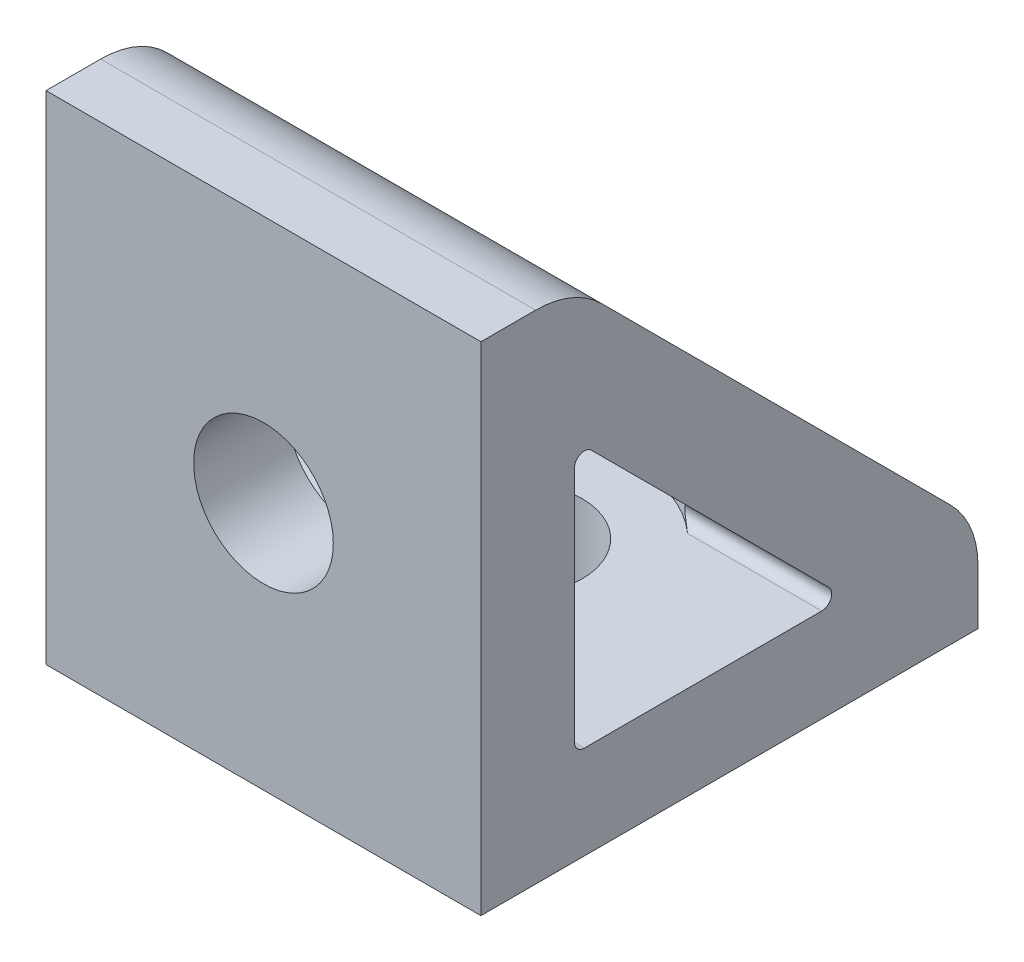
SolidWorks part; units mm, degrees
ref_plane "Front"
ref_plane "Top" through (0, 0, 0) normal (0, 1, 0) x (1, 0, 0)
ref_plane "Right" through (0, 0, 0) normal (1, 0, 0) x (0, 0, -1)
sketch "Sketch1" plane through (0, 0, 0) normal (1, 0, 0) x (0, 0, -1)
  line L0 (11.7094, 11.7094) -> (15.086, 15.086) construction
  line L1 (4.7752, 12.7) -> (0, 12.7) construction
  line L2 (11.3502, 4.7752) -> (11.3502, 0) construction
  line L8 (0, 25.4) -> (0, 0)
  line L9 (0, 0) -> (25.4, 0)
  line L10 (25.4, 0) -> (25.4, 2.794)
  line L11 (4.7752, 17.4172) -> (4.7752, 5.2832)
  line L12 (5.2832, 4.7752) -> (17.4172, 4.7752)
  line L13 (2.794, 25.4) -> (0, 25.4)
  line L14 (6.1706, 24.0014) -> (24.0014, 6.1706)
  line L15 (5.6424, 17.7764) -> (17.7764, 5.6424)
  arc A0 (4.7752, 5.2832) -> (5.2832, 4.7752) centre (5.2832, 5.2832) ccw
  arc A1 (17.4172, 4.7752) -> (17.7764, 5.6424) centre (17.4172, 5.2832) ccw
  arc A2 (5.6424, 17.7764) -> (4.7752, 17.4172) centre (5.2832, 17.4172) ccw
  arc A3 (6.1706, 24.0014) -> (2.794, 25.4) centre (2.794, 20.6248) ccw
  arc A4 (25.4, 2.794) -> (24.0014, 6.1706) centre (20.6248, 2.794) ccw
  dimension "OuterRadius" = 4.7752
  dimension "InnerRadius" = 0.508
  dimension "LengthZ" = 25.4
  dimension "HeightY" = 25.4
  dimension "Thickness" = 4.7752
  dimension "Angle" = 45
  dimension "CornerZ" = 2.794
extrude "Base Extrude" add sketch "Sketch1" against normal blind 22.225
sketch "Sketch2" plane through (0, 0, 0) normal (0, -1, 0) x (1, 0, 0)
  line L1 (-22.225, 0) -> (0, 0) construction
  line L2 (0, 0) -> (0, -25.4) construction
  circle A0 centre (-11.1125, -12.7) radius 3.5687
  dimension "D1" = 7.1374
  dimension "Hole1Z" = 12.7
  dimension "Hole1X" = 11.1125
extrude "Hole1" cut sketch "Sketch2" against normal up to next
sketch "Sketch3" plane through (0, 4.7752, 0) normal (0, 1, 0) x (-1, 0, 0)
  circle A0 centre (11.1125, -12.7) radius 6.35
  dimension "Hole1aDiam" = 12.7
extrude "Hole1a" cut sketch "Sketch3" along normal through all
pattern_linear "Hole1 Pattern" [suppressed]
sketch "Sketch4" plane through (0, 0, 0) normal (0, 0, 1) x (1, 0, 0)
  line L1 (0, 25.4) -> (0, 0) construction
  line L2 (-22.225, 0) -> (0, 0) construction
  circle A0 centre (-11.1125, 12.7) radius 3.5687
  dimension "Hole2Diam" = 7.1374
  dimension "Hole2X" = 11.1125
  dimension "Hole2Y" = 12.7
extrude "Hole2" cut sketch "Sketch4" against normal up to next
sketch "Sketch5" plane through (0, 0, -4.7752) normal (0, 0, -1) x (-1, 0, 0)
  circle A0 centre (11.1125, 12.7) radius 6.35
  dimension "Hole2aDiam" = 12.7
extrude "Hole2a" cut sketch "Sketch5" along normal through all
pattern_linear "Hole2 Pattern" [suppressed]
ref_plane "Mate 1" through (0, 0, 0) normal (0, -1, 0) x (1, 0, 0)
ref_plane "Mate 2" through (0, 0, 0) normal (0, 0, 1) x (1, 0, 0)
ref_plane "Mate 3" through (-19.05, 0, 0) normal (-1, 0, 0) x (0, 0, 1)
ref_plane "Mate 4" through (19.05, 0, 0) normal (-1, 0, 0) x (0, 0, 1)
ref_plane "Mate 5" through (-11.0998, 0, 0) normal (-1, 0, 0) x (0, 0, 1)
ref_plane "Mate 6" through (25.4127, 0, 0) normal (-1, 0, 0) x (0, 0, 1)
